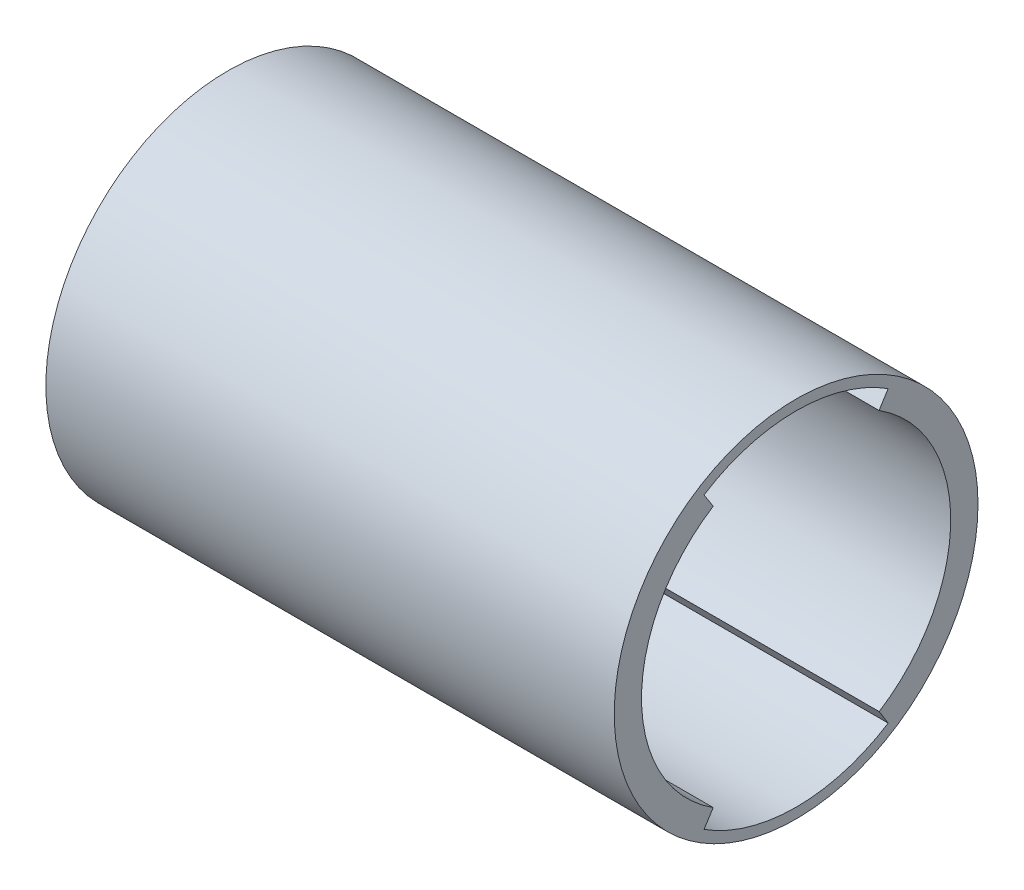
SolidWorks part; units mm, degrees
material "SBR"
ref_plane "Front Plane" through (0, 0, 0) normal (0, 0, 1) x (1, 0, 0)
ref_plane "Top Plane" through (0, 0, 0) normal (0, 1, 0) x (1, 0, 0)
ref_plane "Right Plane" through (0, 0, 0) normal (1, 0, 0) x (0, 0, -1)
sketch "Sketch1" plane through (0, 0, 0) normal (1, 0, 0) x (0, 0, -1)
  circle A0 centre (0, 0) radius 16
  circle A1 centre (0, 0) radius 13.6
  dimension "D1" = 32
  dimension "D2" = 27.2
extrude "Boss-Extrude1" add sketch "Sketch1" along normal blind 50
sketch "Sketch2" plane through (50, 0, 0) normal (1, 0, 0) x (0, 0, -1)
  line L0 (-8.1, 12.7436) -> (-7.2954, 11.4777)
  line L1 (8.1, 12.7436) -> (7.2954, 11.4777)
  line L2 (-8.1, -12.7436) -> (-7.2954, -11.4777)
  line L3 (8.1, -12.7436) -> (7.309, -11.4691)
  circle A1 centre (0, 0) radius 15.1 construction
  circle A2 centre (0, 0) radius 13.6 construction
  arc A3 (-8.1, 12.7436) -> (8.1, 12.7436) centre (0, 0) cw
  arc A4 (-7.2954, 11.4777) -> (7.2954, 11.4777) centre (0, 0) cw
  arc A5 (-8.1, -12.7436) -> (8.1, -12.7436) centre (0, 0) ccw
  arc A6 (-7.2954, -11.4777) -> (7.309, -11.4691) centre (0, 0) ccw
  dimension "D1" = 8.1
  dimension "D2" = 30.2
  dimension "D3" = 8.1
  dimension "D4" = 8.1
  dimension "D5" = 8.1
extrude "Cut-Extrude1" cut sketch "Sketch2" against normal through all
sketch "Sketch3" plane through (0, 0, 0) normal (0, -0.5364, -0.8439) x (-1, 0, 0)
  line L0 (0, -13.6) -> (-50, -13.6) construction
  line L1 (-7, -13.6) -> (-25, -13.6) construction
  line L2 (-7, -13.6) -> (-7, -12.4459)
  line L3 (-7, -12.4459) -> (-25, -12.4459)
  line L4 (-25, -12.4459) -> (-25, -13.6)
  spline S0 degree 3 poles (-25, -13.6) (-25.4196, -14.5332) (-22.2153, -14.2995) (-19.1829, -14.3983) (-18.4286, -14.4147) (-16.2839, -14.3968) (-13.1862, -14.6688) (-11.0281, -13.1265) (-8.8192, -14.9765) (-7, -13.6) knots 0 0 0 0 0.204097 0.238609 0.396579 0.439763 0.627271 0.685639 1 1 1 1
  dimension "D1" = 7
  dimension "D2" = 25
extrude "Cut-Extrude2" cut sketch "Sketch3" against normal blind 3.5
